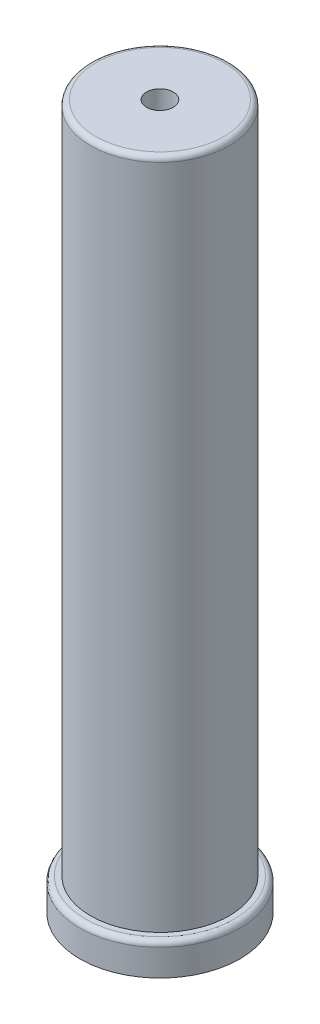
SolidWorks part; units mm, degrees
material "Настроенная пользователем пластмасса"
ref_plane "Front" through (0, 0, 0) normal (0, 0, 1) x (1, 0, 0)
ref_plane "Top" through (0, 0, 0) normal (0, 1, 0) x (1, 0, 0)
ref_plane "Right" through (0, 0, 0) normal (1, 0, 0) x (0, 0, -1)
sketch "Эскиз1" plane through (0, 0, 0) normal (0, 1, 0) x (1, 0, 0)
  circle A0 centre (0, 0) radius 7.5
  circle A1 centre (0, 0) radius 1.25
  dimension "D1" = 2.5
  dimension "D2" = 15
extrude "Бобышка-Вытянуть1" add sketch "Эскиз1" along normal blind 3
sketch "Эскиз2" plane through (0, 3, 0) normal (0, 1, 0) x (1, 0, 0)
  circle A0 centre (0, 0) radius 6.5
  dimension "D1" = 13
extrude "Бобышка-Вытянуть2" add sketch "Эскиз2" along normal blind 63
sketch "Эскиз3" plane through (0, 3, 0) normal (0, -1, 0) x (1, 0, 0)
  circle A0 centre (0, 0) radius 1.25
extrude "Вырез-Вытянуть1" cut sketch "Эскиз3" against normal through all
fillet "Скругление1" radius 0.5 2 edges at (0, 66, 6.5) (0, 3, 7.5)
